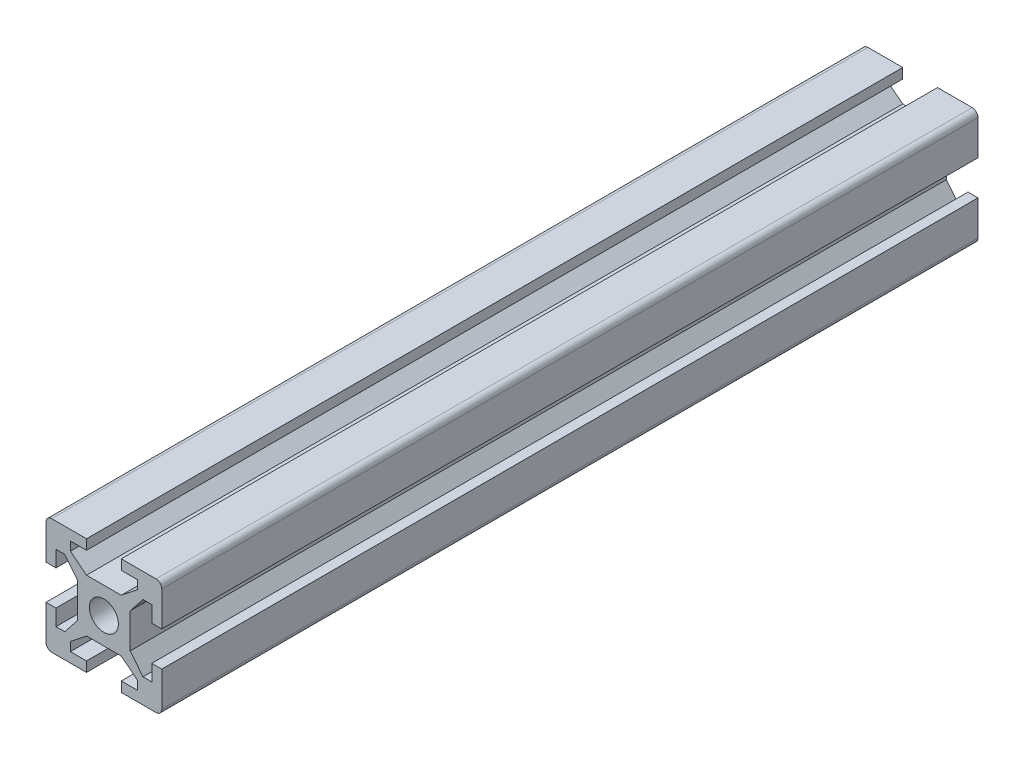
SolidWorks part; units mm, degrees
material "6063-T5"
ref_plane "Front Plane" through (0, 0, 0) normal (0, 0, 1) x (1, 0, 0)
ref_plane "Top Plane" through (0, 0, 0) normal (0, 1, 0) x (1, 0, 0)
ref_plane "Right Plane" through (0, 0, 0) normal (1, 0, 0) x (0, 0, -1)
sketch "Sketch1" plane through (0, 0, 0) normal (0, 0, 1) x (1, 0, 0)
  line L18 (0, 0) -> (0, 20.5117) construction
  line L39 (-10, 10) -> (-3, 10)
  line L41 (10, 10) -> (3, 10)
  line L43 (-10, 10) -> (-10, 3)
  line L45 (-10, -10) -> (-10, -3)
  line L47 (-10, -10) -> (-3, -10)
  line L49 (3, -10) -> (10, -10)
  line L51 (10, -10) -> (10, -3)
  line L53 (10, 3) -> (10, 10)
  line L55 (-3, 10) -> (-3, 8.2726)
  line L56 (-3, 8.2726) -> (-5.7838, 8.2726)
  line L57 (-5.7838, 8.2726) -> (-5.7838, 6.748)
  line L58 (-5.7838, 6.748) -> (-3, 4.5508)
  line L59 (-3, 4.5508) -> (3, 4.5508)
  line L60 (3, 10) -> (3, 8.2726)
  line L61 (3, 8.2726) -> (5.7838, 8.2726)
  line L62 (5.7838, 8.2726) -> (5.7838, 6.748)
  line L63 (5.7838, 6.748) -> (3, 4.5508)
  line L64 (10, 3) -> (8.2726, 3)
  line L65 (8.2726, 3) -> (8.2726, 5.7838)
  line L66 (8.2726, 5.7838) -> (6.748, 5.7838)
  line L67 (10, -3) -> (8.2726, -3)
  line L68 (8.2726, -3) -> (8.2726, -5.7838)
  line L69 (8.2726, -5.7838) -> (6.748, -5.7838)
  line L70 (4.55, -2.9994) -> (4.55, 3.0006)
  line L71 (4.55, -2.9994) -> (6.748, -5.7838)
  line L72 (4.55, 3.0006) -> (6.748, 5.7838)
  line L73 (3, -10) -> (3, -8.2726)
  line L74 (3, -8.2726) -> (5.7838, -8.2726)
  line L75 (5.7838, -8.2726) -> (5.7838, -6.748)
  line L76 (-3, -10) -> (-3, -8.2726)
  line L77 (-3, -8.2726) -> (-5.7838, -8.2726)
  line L78 (-5.7838, -8.2726) -> (-5.7838, -6.748)
  line L79 (2.9994, -4.55) -> (-3.0006, -4.55)
  line L80 (5.7838, -6.748) -> (2.9994, -4.55)
  line L81 (-5.7838, -6.748) -> (-3.0006, -4.55)
  line L82 (-10, -3) -> (-8.2726, -3)
  line L83 (-8.2726, -3) -> (-8.2726, -5.7838)
  line L84 (-8.2726, -5.7838) -> (-6.748, -5.7838)
  line L85 (-10, 3) -> (-8.2726, 3)
  line L86 (-8.2726, 3) -> (-8.2726, 5.7838)
  line L87 (-8.2726, 5.7838) -> (-6.748, 5.7838)
  line L88 (-4.55, -3.0006) -> (-4.55, 2.9994)
  line L89 (-6.748, -5.7838) -> (-4.55, -3.0006)
  line L90 (-4.55, 2.9994) -> (-6.748, 5.7838)
  dimension "D9" = 7
  dimension "D17" = 2.7838
  dimension "D1" = 20
  dimension "D2" = 20
  dimension "D3" = 10
  dimension "D4" = 10
  dimension "D5" = 7
  dimension "D6" = 7
  dimension "D7" = 7
  dimension "D8" = 7
  dimension "D10" = 7
  dimension "D11" = 7
  dimension "D12" = 7
  dimension "D13" = 6
  dimension "D14" = 3
  dimension "D15" = 3.5464
  dimension "D16" = 1.5246
  dimension "D18" = 1.7274
  dimension "D19" = 4.55
  dimension "D20" = 4.55
  dimension "D21" = 4.55
  dimension "D22" = 10
  dimension "D23" = 10
  dimension "D24" = 10
  dimension "D25" = 10
  dimension "D26" = 10
  dimension "D27" = 10
  dimension "D28" = 6
  dimension "D29" = 6
  dimension "D30" = 6
  dimension "D31" = 6
extrude "Boss-Extrude1" add sketch "Sketch1" along normal mid plane 141
sketch "Sketch2" plane through (0, 0, 70.5) normal (0, 0, 1) x (1, 0, 0)
  circle A0 centre (0, 0) radius 2.5
  dimension "D1" = 5
extrude "Cut-Extrude1" cut sketch "Sketch2" against normal through all both and the other way through all
fillet "Fillet1" radius 1 4 edges at (-10, -10, 0) (10, -10, 0) (10, 10, 0) (-10, 10, 0)
